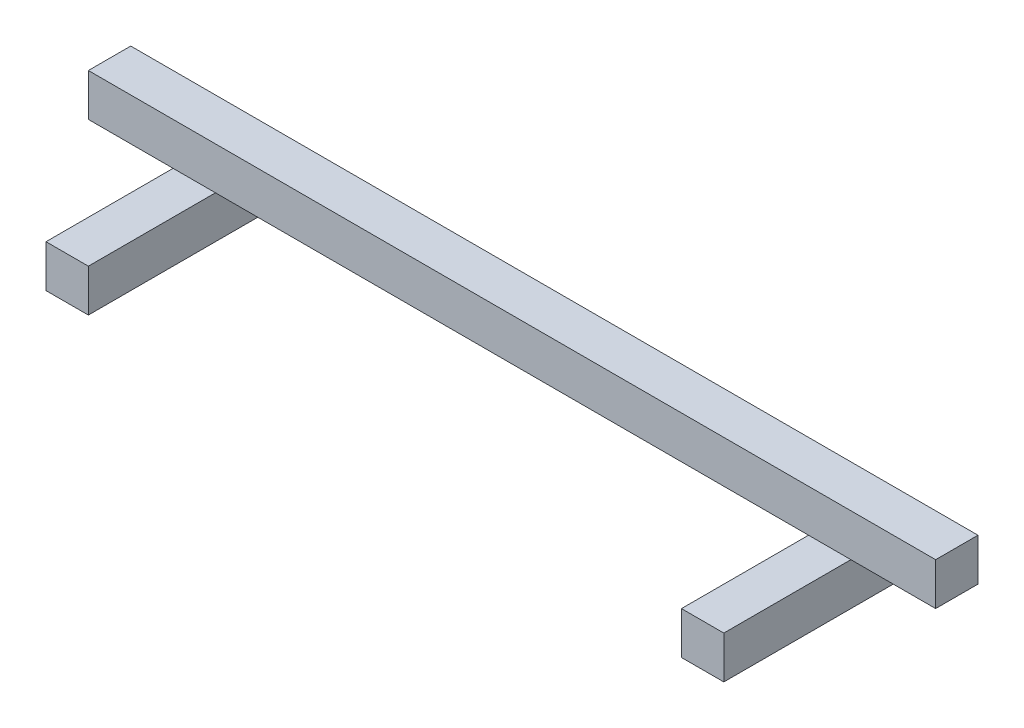
SolidWorks part; units mm, degrees
material "6061-T6 (SS)"
ref_plane "Front Plane" through (0, 0, 0) normal (0, 0, 1) x (1, 0, 0)
ref_plane "Top Plane" through (0, 0, 0) normal (0, 1, 0) x (1, 0, 0)
ref_plane "Right Plane" through (0, 0, 0) normal (1, 0, 0) x (0, 0, -1)
sketch "Sketch5" plane through (0, 0, 0) normal (0, 1, 0) x (1, 0, 0)
  line L1 (-381, 19.05) -> (381, 19.05)
  line L2 (-381, 19.05) -> (-381, -19.05)
  line L3 (-381, -19.05) -> (381, -19.05)
  line L4 (381, 19.05) -> (381, -19.05)
  point P4 (0, -19.05)
  point P5 (381, 0)
  dimension "D1" = 38.1
  dimension "D2" = 762
extrude "Boss-Extrude3" add sketch "Sketch5" along normal blind 38.1 separate body
sketch "Sketch4" plane through (0, 0, -19.05) normal (0, 0, 1) x (1, 0, 0)
  line L0 (0, -49.8154) -> (0, -157.6436) construction
  line L1 (-381, 0) -> (381, 0) construction
  line L2 (266.7, 0) -> (266.7, -38.1)
  line L3 (-304.8, 0) -> (-266.7, 0)
  line L4 (-304.8, 0) -> (-304.8, -38.1)
  line L5 (-304.8, -38.1) -> (-266.7, -38.1)
  line L6 (-266.7, 0) -> (-266.7, -38.1)
  line L7 (304.8, -38.1) -> (266.7, -38.1)
  line L8 (304.8, 0) -> (304.8, -38.1)
  line L9 (304.8, 0) -> (266.7, 0)
  dimension "D1" = 38.1
  dimension "D2" = 609.6
extrude "Boss-Extrude4" add sketch "Sketch4" along normal blind 152.4 separate body
